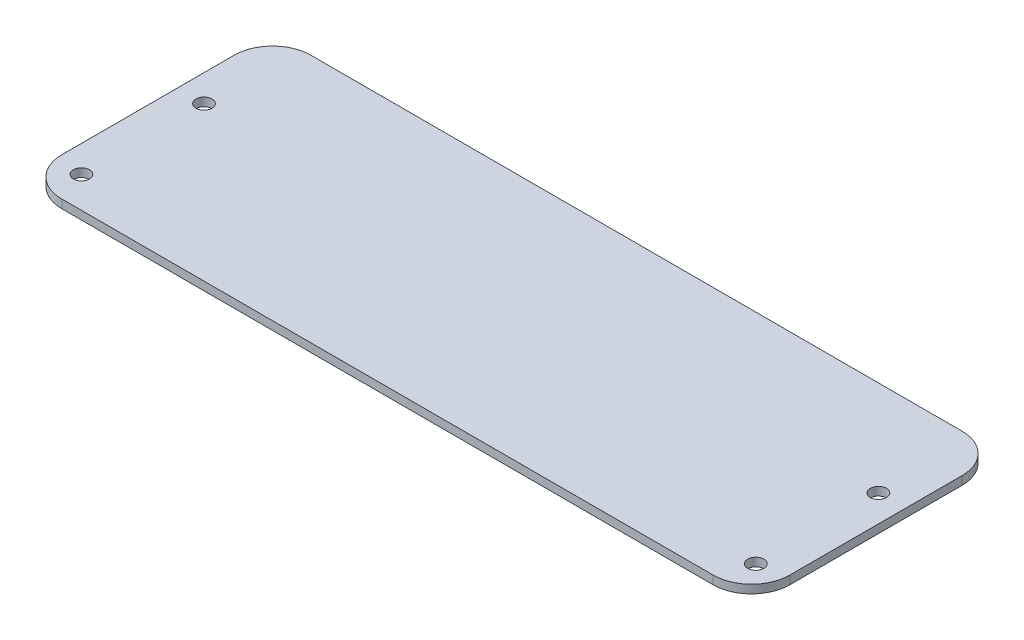
SolidWorks part; units mm, degrees
ref_plane "Front" through (0, 0, 0) normal (0, 0, 1) x (1, 0, 0)
ref_plane "Top" through (0, 0, 0) normal (0, 1, 0) x (1, 0, 0)
ref_plane "Right" through (0, 0, 0) normal (1, 0, 0) x (0, 0, -1)
sketch "Sketch1" plane through (0, 0, 0) normal (0, 1, 0) x (1, 0, 0)
  line L0 (0, 0) -> (0, 50000) construction
  line L1 (-95, -32.5) -> (95, -32.5)
  line L2 (-95, -32.5) -> (-95, 32.5)
  line L3 (-95, 32.5) -> (95, 32.5)
  line L4 (95, -32.5) -> (95, 32.5)
  circle A0 centre (-88, 7.6232) radius 2.1
  circle A1 centre (-88, -24.3768) radius 2.1
  circle A2 centre (88, -24.3768) radius 2.1
  circle A3 centre (88, 7.6232) radius 2.1
  point P0 (0, 0)
  point P5 (0, 0)
extrude "Boss-Extrude1" add sketch "Sketch1" along normal blind 2.2
fillet "Fillet1" radius 10 4 edges at (95, 1.1, 32.5) (-95, 1.1, 32.5) (95, 1.1, -32.5) (-95, 1.1, -32.5)
